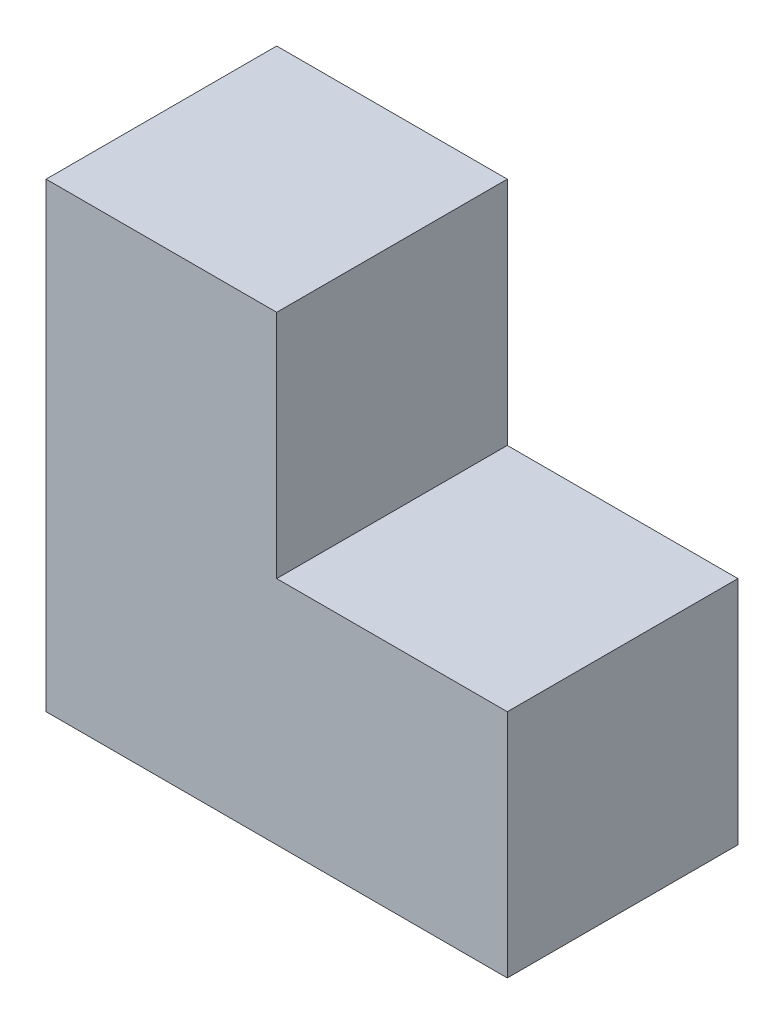
SolidWorks part; units mm, degrees
ref_plane "Plan de face" through (0, 0, 0) normal (0, 0, 1) x (1, 0, 0)
ref_plane "Plan de dessus" through (0, 0, 0) normal (0, 1, 0) x (1, 0, 0)
ref_plane "Plan de droite" through (0, 0, 0) normal (1, 0, 0) x (0, 0, -1)
sketch "Esquisse1" plane through (0, 0, 0) normal (0, 0, 1) x (1, 0, 0)
  line L0 (0, 0) -> (0, 20)
  line L1 (0, 20) -> (10, 20)
  line L2 (10, 20) -> (10, 10)
  line L3 (20, 0) -> (20, 10)
  line L4 (0, 0) -> (20, 0)
  line L5 (20, 10) -> (10, 10)
  dimension "D1" = 10
  dimension "D2" = 20
  dimension "D3" = 20
  dimension "D4" = 10
extrude "Boss.-Extru.1" add sketch "Esquisse1" against normal blind 10
